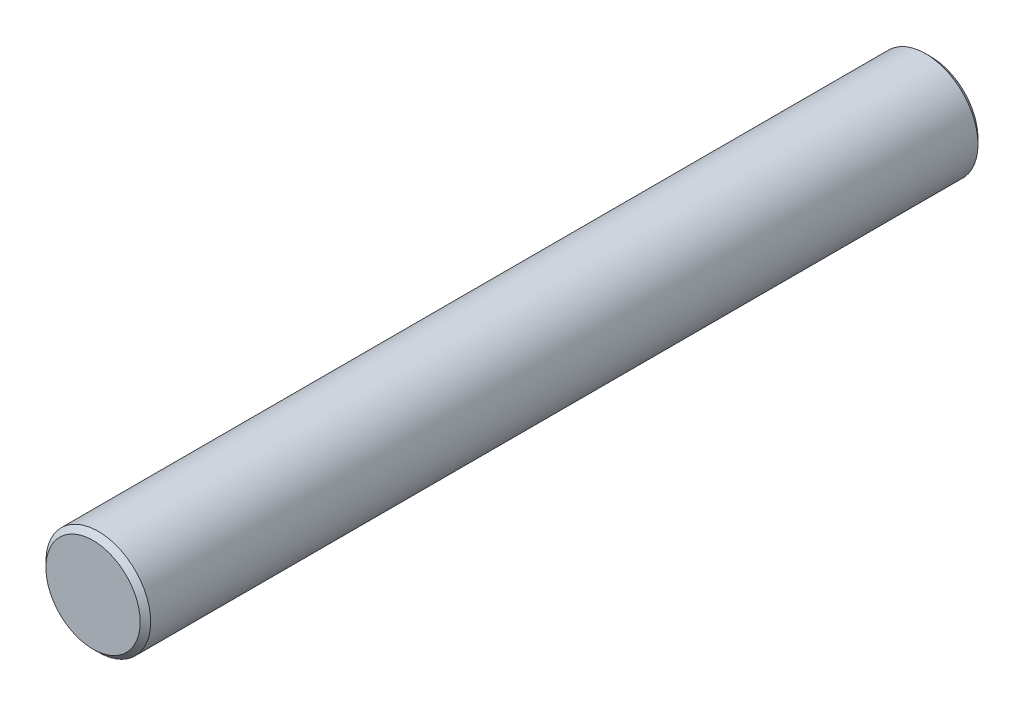
SolidWorks part; units mm, degrees
ref_plane "前视基准面" through (0, 0, 0) normal (0, 0, 1) x (1, 0, 0)
ref_plane "上视基准面" through (0, 0, 0) normal (0, 1, 0) x (1, 0, 0)
ref_plane "右视基准面" through (0, 0, 0) normal (1, 0, 0) x (0, 0, -1)
sketch "草图1" plane through (0, 0, 0) normal (0, 0, 1) x (1, 0, 0)
  circle A0 centre (0, 0) radius 5
extrude "拉伸1" add sketch "草图1" along normal blind 80
hole_wizard "M5 螺纹孔1" positions "草图3" profile "草图2" tap size "M5" standard "GB"
sketch "草图3" plane through (0, 0, 0) normal (0, 0, -1) x (-1, 0, 0)
  point P0 (0, 0)
sketch "草图2" plane through (0, 0, 0) normal (1, 0, 0) x (0, 1, 0)
  line L0 (0, 0) -> (0, 18.6618)
  line L1 (0, 18.6618) -> (2.1, 17.4)
  line L2 (2.1, 17.4) -> (2.1, 15)
  line L3 (2.1, 15) -> (2.5, 15)
  line L4 (2.5, 15) -> (2.5, 0)
  line L5 (2.5, 0) -> (0, 0)
  line L10 (0, 18.6618) -> (-2.1, 17.4) construction
  line L11 (0, -6.35) -> (0, 107.95) construction
  dimension "螺纹孔钻头直径" = 4.2
  dimension "螺纹孔钻头深度" = 17.4
  dimension "螺纹主直径" = 5
  dimension "螺纹深度" = 15
  dimension "导头角度" = 118
chamfer "倒角1" distance 0.5 angle 45 2 edges at (5, 0, 0) (5, 0, 80)
